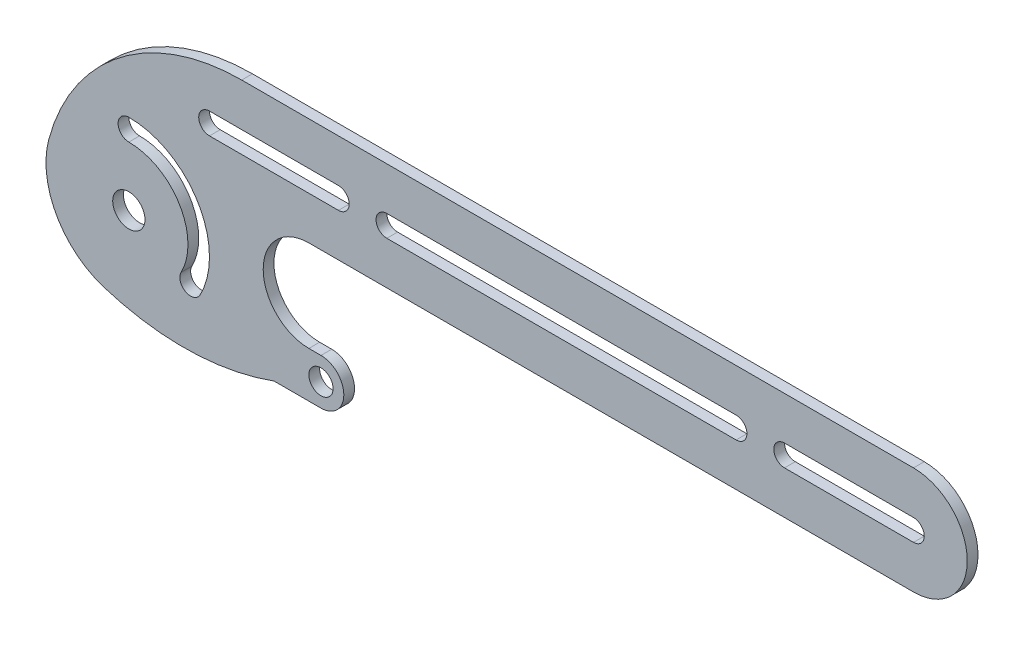
SolidWorks part; units mm, degrees
ref_plane "Plan de face" through (0, 0, 0) normal (0, 0, 1) x (1, 0, 0)
ref_plane "Plan de dessus" through (0, 0, 0) normal (0, 1, 0) x (1, 0, 0)
ref_plane "Plan de droite" through (0, 0, 0) normal (1, 0, 0) x (0, 0, -1)
sketch "Esquisse1" plane through (0, 0, 0) normal (0, 0, 1) x (1, 0, 0)
  line L0 (21, 31.5) -> (146, 31.5)
  line L1 (146, 11.5) -> (33.5, 11.5)
  line L2 (33.5, -5.5) -> (35.75, -5.5)
  line L3 (27, -14) -> (35.75, -14)
  line L4 (15, 21.5) -> (39, 21.5) construction
  line L5 (15, 23.5) -> (39, 23.5)
  line L6 (15, 19.5) -> (39, 19.5)
  line L7 (48, 21.5) -> (113, 21.5) construction
  line L8 (48, 23.5) -> (113, 23.5)
  line L9 (48, 19.5) -> (113, 19.5)
  line L10 (122, 21.5) -> (146, 21.5) construction
  line L11 (122, 23.5) -> (146, 23.5)
  line L12 (122, 19.5) -> (146, 19.5)
  line L13 (0, 13) -> (0, 31.5) construction
  line L14 (15, 61.27) -> (15, -29.927) construction
  line L15 (59.8324, -17) -> (-35.1453, -17) construction
  line L16 (-15.4203, 24.2165) -> (-15.4203, -7.7708) construction
  arc A0 (146, 31.5) -> (146, 11.5) centre (146, 21.5) cw
  arc A1 (33.5, 11.5) -> (33.5, -5.5) centre (33.5, 3) ccw
  arc A2 (35.75, -5.5) -> (35.75, -14) centre (35.75, -9.75) cw
  arc A3 (27, -14) -> (-4.6863, -14.6909) centre (10.1502, 31.8194) cw
  arc A4 (-14.8866, 4.0216) -> (21, 31.5) centre (21, -5.6731) cw
  circle A5 centre (35.75, -9.75) radius 2.25
  circle A6 centre (0, 0) radius 3
  arc A7 (15, 23.5) -> (15, 19.5) centre (15, 21.5) ccw
  arc A8 (39, 19.5) -> (39, 23.5) centre (39, 21.5) ccw
  arc A9 (48, 23.5) -> (48, 19.5) centre (48, 21.5) ccw
  arc A10 (113, 19.5) -> (113, 23.5) centre (113, 21.5) ccw
  arc A11 (122, 23.5) -> (122, 19.5) centre (122, 21.5) ccw
  arc A12 (146, 19.5) -> (146, 23.5) centre (146, 21.5) ccw
  arc A13 (0, 13) -> (11.4976, -6.0667) centre (0, 0) cw construction
  arc A14 (13.2665, -7) -> (0, 15) centre (0, 0) ccw
  arc A15 (9.7288, -5.1333) -> (0, 11) centre (0, 0) ccw
  arc A16 (9.7288, -5.1333) -> (13.2665, -7) centre (11.4976, -6.0667) ccw
  arc A17 (0, 15) -> (0, 11) centre (0, 13) ccw
  arc A18 (-14.8866, 4.0216) -> (-4.6863, -14.6909) centre (0, 0) ccw
  point P11 (120, 21.5)
  point P21 (27, 21.5)
  point P26 (80.5, 21.5)
  point P33 (134, 21.5)
  point P41 (11.1325, 6.7132)
  point P46 (115, 21.5)
  point P47 (46, 21.5)
  point P48 (13, 21.5)
  point P49 (41, 21.5)
  point P50 (0, 25)
  point P51 (25, 3)
  point P52 (148, 21.5)
  point P58 (10.1502, -17)
  point P61 (15, 0)
  point P66 (-15.4203, 0)
  point P76 (40, -9.75)
  dimension "D9" = 8.5
  dimension "D10" = 4.5
  dimension "D16" = 10
  dimension "D17" = 10
  dimension "D22" = 6
  dimension "D1" = 20
  dimension "D2" = 4
  dimension "D3" = 28
  dimension "D4" = 69
  dimension "D5" = 28
  dimension "D6" = 5
  dimension "D7" = 5
  dimension "D8" = 125
  dimension "D11" = 8.5
  dimension "D12" = 25
  dimension "D13" = 3
  dimension "D14" = 4
  dimension "D15" = 10
  dimension "D18" = 13
  dimension "D19" = 40
  dimension "D20" = 13
  dimension "D21" = 17
extrude "Boss.-Extru.1" add sketch "Esquisse1" along normal mid plane 2
ref_plane "Plan1" through (0, 21.5, 0) normal (0, 1, 0) x (1, 0, 0)
